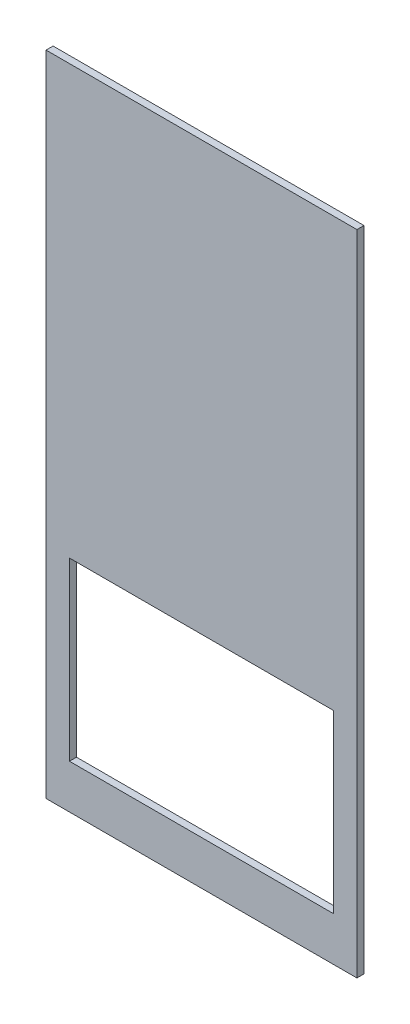
SolidWorks part; units mm, degrees
material "Carvalho"
ref_plane "Plano frontal" through (0, 0, 0) normal (0, 0, 1) x (1, 0, 0)
ref_plane "Plano superior" through (0, 0, 0) normal (0, 1, 0) x (1, 0, 0)
ref_plane "Plano direito" through (0, 0, 0) normal (1, 0, 0) x (0, 0, -1)
sketch "Esboço1" plane through (0, 0, 0) normal (0, 0, 1) x (1, 0, 0)
  line L1 (0, 0) -> (265, 0)
  line L2 (0, 0) -> (0, 552.5)
  line L3 (0, 552.5) -> (265, 552.5)
  line L4 (265, 0) -> (265, 552.5)
  line L5 (20, 187.5) -> (245, 187.5)
  line L6 (20, 187.5) -> (20, 37.5)
  line L7 (20, 37.5) -> (245, 37.5)
  line L8 (245, 187.5) -> (245, 37.5)
  dimension "D1" = 552.5
  dimension "D2" = 265
  dimension "D3" = 225
  dimension "D4" = 20
  dimension "D5" = 37.5
  dimension "D6" = 150
extrude "Ressalto-extrusão1" add sketch "Esboço1" along normal blind 6
